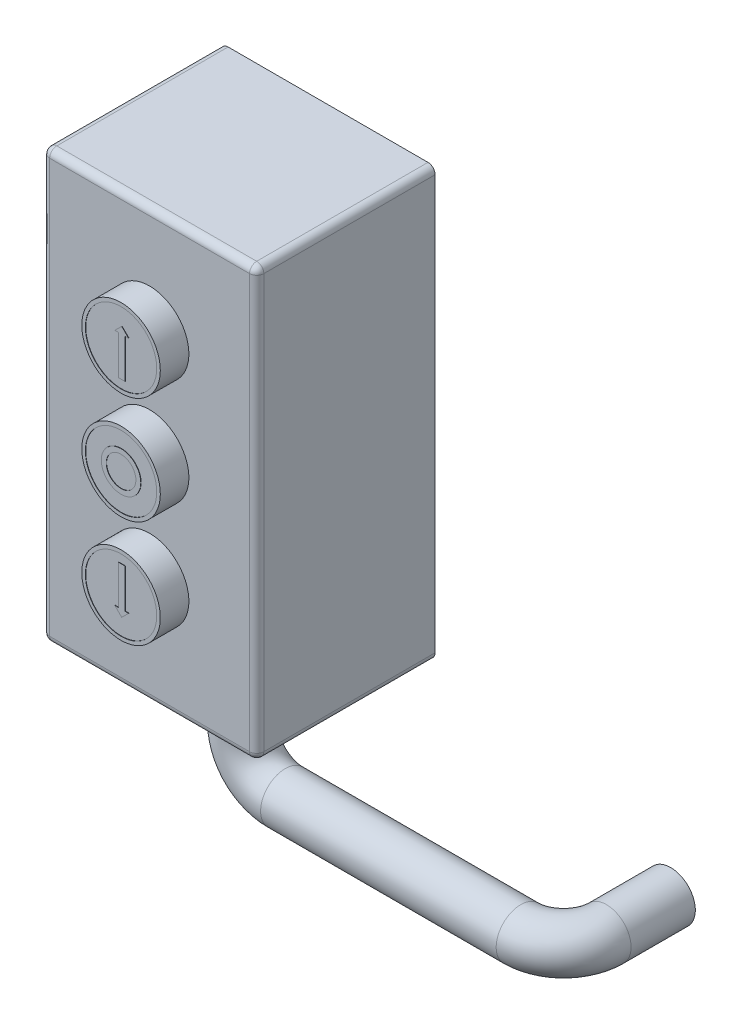
SolidWorks part; units mm, degrees
ref_plane "Alzado" through (0, 0, 0) normal (0, 0, 1) x (1, 0, 0)
ref_plane "Planta" through (0, 0, 0) normal (0, 1, 0) x (1, 0, 0)
ref_plane "Vista lateral" through (0, 0, 0) normal (1, 0, 0) x (0, 0, -1)
sketch "Croquis1" plane through (0, 0, 0) normal (0, 0, 1) x (1, 0, 0)
  line L1 (0, 0) -> (60, 0)
  line L2 (0, 0) -> (0, 120)
  line L3 (0, 120) -> (60, 120)
  line L4 (60, 0) -> (60, 120)
  dimension "D1" = 60
  dimension "D2" = 120
extrude "Saliente-Extruir1" add sketch "Croquis1" along normal blind 50
sketch "Croquis2" plane through (0, 0, 50) normal (0, 0, 1) x (1, 0, 0)
  line L0 (30, 120) -> (30, 60) construction
  line L1 (60, 120) -> (0, 120) construction
  line L2 (30, 60) -> (60, 60) construction
  line L3 (60, 0) -> (60, 120) construction
  circle A0 centre (30, 60) radius 11
  circle A1 centre (30, 90) radius 11
  circle A2 centre (30, 30) radius 11
  dimension "D1" = 22
  dimension "D2" = 22
extrude "Saliente-Extruir2" add sketch "Croquis2" along normal blind 8
sketch "Croquis3" plane through (0, 0, 58) normal (0, 0, 1) x (1, 0, 0)
  circle A0 centre (30, 90) radius 10
  circle A1 centre (30, 60) radius 10
  circle A2 centre (30, 30) radius 10
  dimension "D1" = 20
  dimension "D2" = 20
  dimension "D3" = 20
extrude "Cortar-Extruir1" cut sketch "Croquis3" against normal blind 0.1
sketch "Croquis4" plane through (0, 0, 57.9) normal (0, 0, 1) x (1, 0, 0)
  line L0 (29.277, 94.393) -> (31.0976, 94.393) construction
  line L1 (29.277, 82.393) -> (31.0976, 82.393)
  line L2 (29.277, 82.393) -> (29.277, 93.3691)
  line L3 (29.277, 94.393) -> (30.1873, 95.3033)
  line L4 (31.0976, 82.393) -> (31.0976, 93.3691)
  line L5 (29.277, 82.393) -> (30.4175, 94.393) construction
  line L6 (29.3661, 94.393) -> (31.0976, 82.393) construction
  line L7 (30.1873, 95.3033) -> (31.0976, 94.393)
  line L8 (31.0976, 94.393) -> (32.1215, 93.3691)
  line L9 (32.1215, 93.3691) -> (31.0976, 93.3691)
  line L10 (28.2531, 93.3691) -> (29.277, 94.393)
  line L11 (0, 60) -> (19, 60) construction
  line L12 (0, 120) -> (0, 0) construction
  line L13 (29.3661, 25.607) -> (31.0976, 37.607) construction
  line L14 (29.277, 37.607) -> (30.4175, 25.607) construction
  line L15 (29.277, 25.607) -> (31.0976, 25.607) construction
  line L16 (29.277, 26.6309) -> (28.2531, 26.6309)
  line L17 (28.2531, 26.6309) -> (29.277, 25.607)
  line L18 (32.1215, 26.6309) -> (31.0976, 26.6309)
  line L19 (31.0976, 25.607) -> (32.1215, 26.6309)
  line L20 (30.1873, 24.6967) -> (31.0976, 25.607)
  line L21 (31.0976, 37.607) -> (31.0976, 26.6309)
  line L22 (29.277, 25.607) -> (30.1873, 24.6967)
  line L23 (29.277, 37.607) -> (29.277, 26.6309)
  line L24 (29.277, 93.3691) -> (28.2531, 93.3691)
  line L25 (29.277, 37.607) -> (31.0976, 37.607)
  circle A0 centre (30, 60) radius 11 construction
  point P0 (30, 90)
  point P27 (30, 30)
  dimension "D1" = 12
extrude "Saliente-Extruir3" add sketch "Croquis4" along normal blind 0.1
sketch "Croquis5" plane through (0, 0, 57.9) normal (0, 0, 1) x (1, 0, 0)
  circle A0 centre (30, 60) radius 5.5304
  circle A1 centre (30, 60) radius 4.1547
extrude "Saliente-Extruir4" add sketch "Croquis5" along normal blind 0.1
fillet "Redondeo1" radius 2 8 edges at (0, 120, 25) (60, 120, 25) (0, 0, 25) (60, 0, 25) (30, 0, 50) (30, 120, 50) (0, 60, 50) (60, 60, 50)
sketch "Croquis6" plane through (0, 0, 0) normal (0, -1, 0) x (1, 0, 0)
  line L0 (2, 24) -> (58, 24) construction
  line L1 (2, 48) -> (2, 0) construction
  line L2 (58, 0) -> (58, 48) construction
  circle A0 centre (30, 24) radius 9
  dimension "D1" = 18
extrude "Saliente-Extruir5" add sketch "Croquis6" along normal blind 10
chamfer "Chaflán1" distance 3 angle 35 1 edges at (30, -10, 15)
sketch3d "Croquis3D1"
  line L0 (30, -10, 24) -> (30, -18, 24)
  line L1 (30, -7, 24) -> (30, -10, 24) construction
  line L2 (42, -30, 24) -> (108, -30, 24)
  line L3 (120, -30, 12) -> (120, -30, -6)
  arc A0 (108, -30, 24) -> (120, -30, 12) centre (108, -30, 12) ccw
  arc A1 (30, -18, 24) -> (42, -30, 24) centre (42, -18, 24) ccw
  point P8 (120, -30, 24)
  point P9 (108, -18, 12)
  point P12 (30, -30, 24)
  point P13 (42, -18, 36)
  dimension "D4" = 12
  dimension "D1" = 20
  dimension "D2" = 90
  dimension "D3" = 30
sketch "Croquis8" plane through (0, -10, 0) normal (0, -1, 0) x (1, 0, 0)
  circle A0 centre (30, 24) radius 6.8994
sweep "Barrer1" add profiles "Croquis8" path "Croquis3D1"
